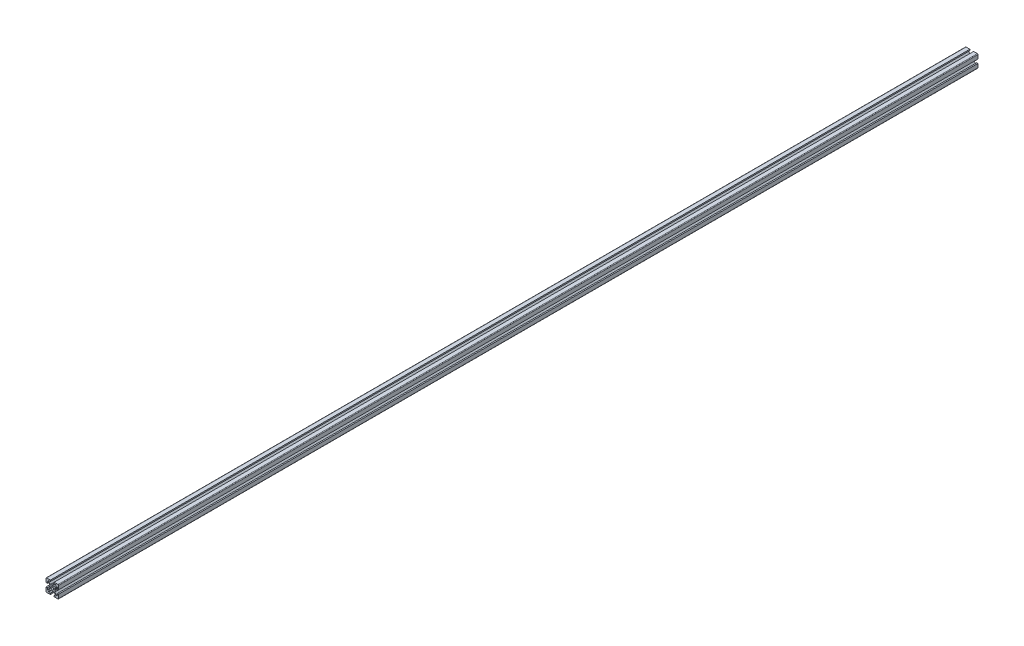
SolidWorks part; units mm, degrees
ref_plane "前基準面" through (0, 0, 0) normal (0, 0, 1) x (1, 0, 0)
ref_plane "上基準面" through (0, 0, 0) normal (0, 1, 0) x (1, 0, 0)
ref_plane "右基準面" through (0, 0, 0) normal (1, 0, 0) x (0, 0, -1)
ref_plane "平面1" through (0, 0, -2500) normal (0, 0, -1) x (-1, 0, 0)
sketch "草圖1" plane through (0, 0, -2500) normal (0, 0, -1) x (-1, 0, 0)
  line L0 (10, -3) -> (8, -3)
  line L1 (8, -3) -> (8, -6)
  line L2 (8, -6) -> (7.0607, -6)
  line L3 (7.0607, -6) -> (4, -2.9393)
  line L4 (4, -2.9393) -> (4, -2.5)
  line L5 (4, -2.5) -> (3.751, -1.2189)
  line L6 (3.751, -1.2189) -> (3.933, -0.9036)
  line L7 (3.933, -0.4036) -> (3.7, 0)
  line L8 (3.7, 0) -> (3.933, 0.4036)
  line L9 (4, 0.6536) -> (4, 2.9393)
  line L10 (4, 2.9393) -> (7.0607, 6)
  line L11 (7.0607, 6) -> (8, 6)
  line L12 (8, 6) -> (8, 3)
  line L13 (8, 3) -> (10, 3)
  line L14 (10, 3) -> (10, 9)
  line L15 (9, 10) -> (3, 10)
  line L16 (3, 10) -> (3, 8)
  line L17 (3, 8) -> (6, 8)
  line L18 (6, 8) -> (6, 7.0607)
  line L19 (6, 7.0607) -> (2.9393, 4)
  line L20 (2.9393, 4) -> (2.5, 4)
  line L21 (2.5, 4) -> (1.2189, 3.751)
  line L22 (1.2189, 3.751) -> (0.9036, 3.933)
  line L23 (0.4036, 3.933) -> (0, 3.7)
  line L24 (0, 3.7) -> (-0.4036, 3.933)
  line L25 (-0.6536, 4) -> (-2.9393, 4)
  line L26 (-2.9393, 4) -> (-6, 7.0607)
  line L27 (-6, 7.0607) -> (-6, 8)
  line L28 (-6, 8) -> (-3, 8)
  line L29 (-3, 8) -> (-3, 10)
  line L30 (-3, 10) -> (-9, 10)
  line L31 (-10, 9) -> (-10, 3)
  line L32 (-10, 3) -> (-8, 3)
  line L33 (-8, 3) -> (-8, 6)
  line L34 (-8, 6) -> (-7.0607, 6)
  line L35 (-7.0607, 6) -> (-4, 2.9393)
  line L36 (-4, 2.9393) -> (-4, 2.5)
  line L37 (-4, 2.5) -> (-3.751, 1.2189)
  line L38 (-3.751, 1.2189) -> (-3.933, 0.9036)
  line L39 (-3.933, 0.4036) -> (-3.7, 0)
  line L40 (-3.7, 0) -> (-3.933, -0.4036)
  line L41 (-4, -0.6536) -> (-4, -2.9393)
  line L42 (-4, -2.9393) -> (-7.0607, -6)
  line L43 (-7.0607, -6) -> (-8, -6)
  line L44 (-8, -6) -> (-8, -3)
  line L45 (-8, -3) -> (-10, -3)
  line L46 (-10, -3) -> (-10, -9)
  line L47 (-9, -10) -> (-3, -10)
  line L48 (-3, -10) -> (-3, -8)
  line L49 (-3, -8) -> (-6, -8)
  line L50 (-6, -8) -> (-6, -7.0607)
  line L51 (-6, -7.0607) -> (-2.9393, -4)
  line L52 (-2.9393, -4) -> (-2.5, -4)
  line L53 (-2.5, -4) -> (-1.2189, -3.751)
  line L54 (-1.2189, -3.751) -> (-0.9036, -3.933)
  line L55 (-0.4036, -3.933) -> (0, -3.7)
  line L56 (0, -3.7) -> (0.4036, -3.933)
  line L57 (0.6536, -4) -> (2.9393, -4)
  line L58 (2.9393, -4) -> (6, -7.0607)
  line L59 (6, -7.0607) -> (6, -8)
  line L60 (6, -8) -> (3, -8)
  line L61 (3, -8) -> (3, -10)
  line L62 (3, -10) -> (9, -10)
  line L63 (10, -9) -> (10, -3)
  circle A0 centre (0, 0) radius 2.1
  arc A1 (3.933, -0.9036) -> (3.933, -0.4036) centre (3.5, -0.6536) ccw
  arc A2 (3.933, 0.4036) -> (4, 0.6536) centre (3.5, 0.6536) ccw
  arc A3 (10, 9) -> (9, 10) centre (9, 9) ccw
  arc A4 (0.9036, 3.933) -> (0.4036, 3.933) centre (0.6536, 3.5) ccw
  arc A5 (-0.4036, 3.933) -> (-0.6536, 4) centre (-0.6536, 3.5) ccw
  arc A6 (-9, 10) -> (-10, 9) centre (-9, 9) ccw
  arc A7 (-3.933, 0.9036) -> (-3.933, 0.4036) centre (-3.5, 0.6536) ccw
  arc A8 (-3.933, -0.4036) -> (-4, -0.6536) centre (-3.5, -0.6536) ccw
  arc A9 (-10, -9) -> (-9, -10) centre (-9, -9) ccw
  arc A10 (-0.9036, -3.933) -> (-0.4036, -3.933) centre (-0.6536, -3.5) ccw
  arc A11 (0.4036, -3.933) -> (0.6536, -4) centre (0.6536, -3.5) ccw
  arc A12 (9, -10) -> (10, -9) centre (9, -9) ccw
extrude "填料-伸長1" add sketch "草圖1" against normal blind 1460
